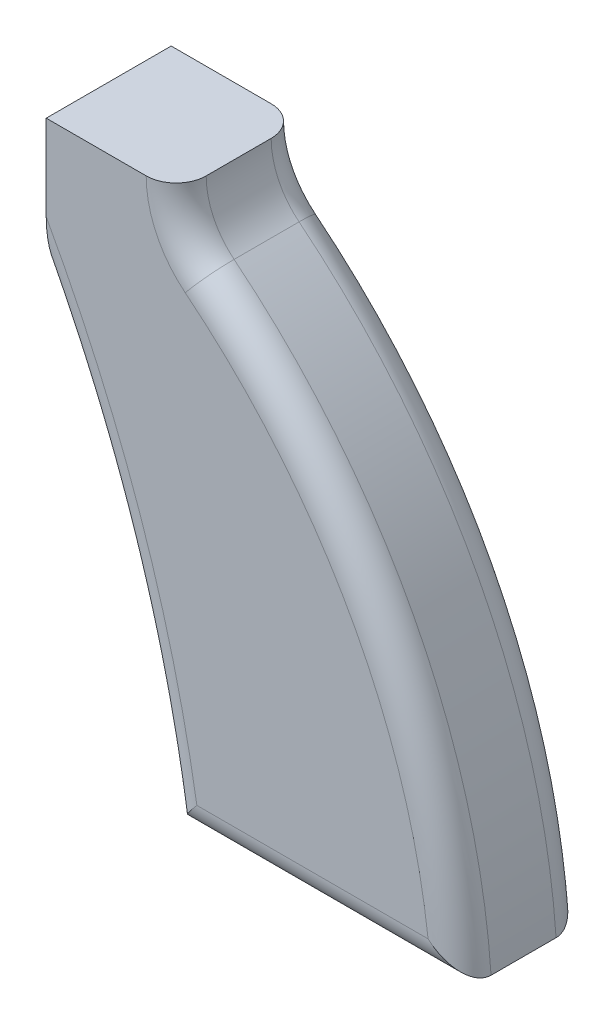
SolidWorks part; units mm, degrees
ref_plane "前视基准面" through (0, 0, 0) normal (0, 0, 1) x (1, 0, 0)
ref_plane "上视基准面" through (0, 0, 0) normal (0, 1, 0) x (1, 0, 0)
ref_plane "右视基准面" through (0, 0, 0) normal (1, 0, 0) x (0, 0, -1)
other "Configuration Table"
sketch "草图1" plane through (0, 0, 0) normal (0, 0, 1) x (1, 0, 0)
  line L0 (0, 0) -> (26, 0)
  line L1 (83, -110) -> (25, -110)
  line L2 (0, -30) -> (0, 0)
  arc A0 (26, 0) -> (31.5863, -11.6783) centre (41, 0) ccw
  arc A1 (31.5863, -11.6783) -> (83, -110) centre (-55.6472, -119.8971) cw
  arc A2 (25, -110) -> (0, -30) centre (-237.2543, -148.0482) ccw
  point P10 (41.2148, -23.8333)
  point P11 (40.987, -0.6244)
  point P12 (0, 0)
  dimension "D3" = 15
  dimension "D4" = 110
  dimension "D7" = 139
  dimension "D8" = 265
  dimension "D1" = 26
  dimension "D2" = 30
  dimension "D5" = 25
  dimension "D6" = 58
extrude "凸台-拉伸1" add sketch "草图1" along normal mid plane 25
fillet "圆角1" radius 6 8 edges at (27.4685, -6.4728, -12.5) (27.4685, -6.4728, 12.5) (54, -110, -12.5) (54, -110, 12.5) (15.6829, -69.0054, -12.5) (15.6829, -69.0054, 12.5) (67.5287, -55.4868, -12.5) (67.5287, -55.4868, 12.5)
